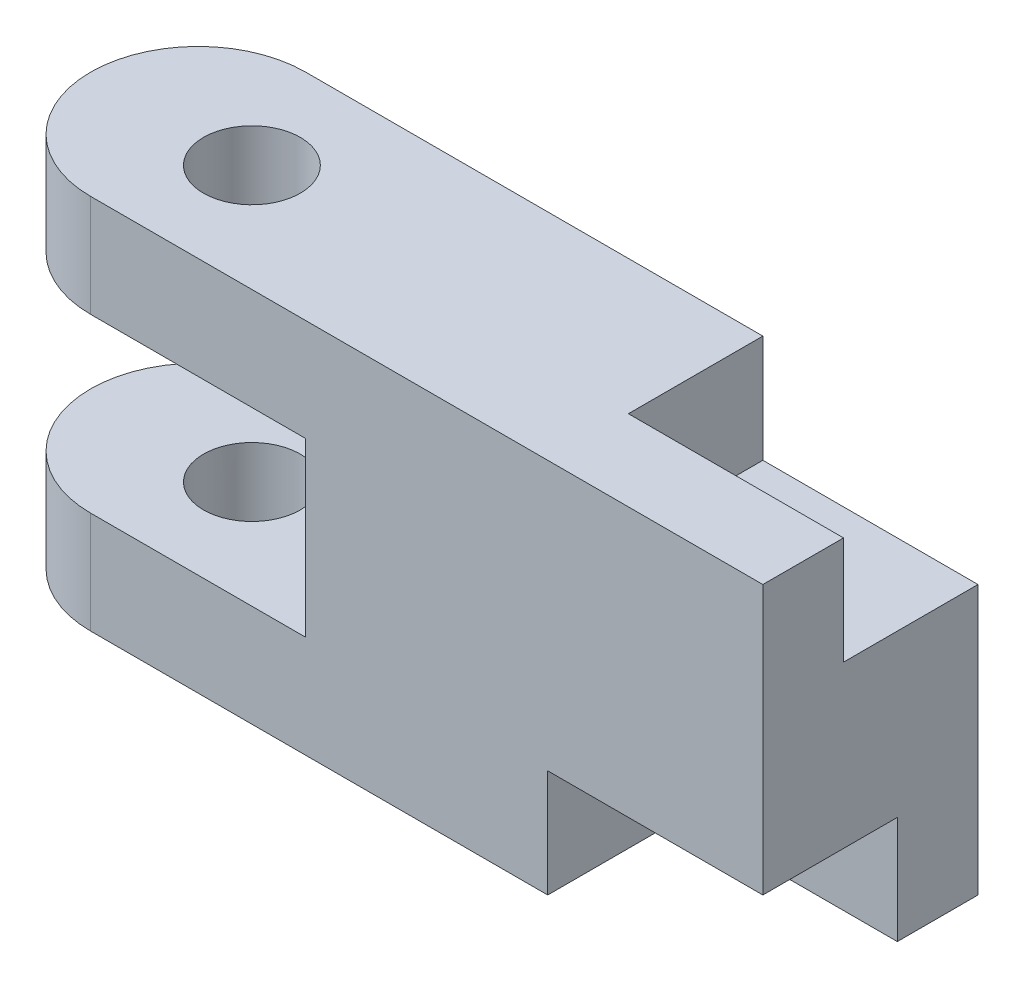
SolidWorks part; units mm, degrees
ref_plane "Front Plane" through (0, 0, 0) normal (0, 0, 1) x (1, 0, 0)
ref_plane "Top Plane" through (0, 0, 0) normal (0, 1, 0) x (1, 0, 0)
ref_plane "Right Plane" through (0, 0, 0) normal (1, 0, 0) x (0, 0, -1)
sketch "Sketch1" plane through (0, 0, 0) normal (0, 1, 0) x (1, 0, 0)
  line L1 (-1, 2) -> (11.5, 2)
  line L3 (-1, -2) -> (11.5, -2)
  line L4 (11.5, 2) -> (11.5, -2)
  line L5 (5.25, -2) -> (5.25, 2) construction
  line L6 (0, 0) -> (11.5, 0) construction
  circle A0 centre (0, 0) radius 0.9
  arc A2 (-1, 2) -> (-1, -2) centre (-1, 0) ccw
  point P315 (5.25, 0)
  dimension "D1" = 1.8
  dimension "D5" = 2
  dimension "D2" = 4
  dimension "D3" = 12.5
  dimension "D4" = 1
extrude "Boss-Extrude1" add sketch "Sketch1" along normal blind 7
sketch "Sketch2" plane through (0, 0, 2) normal (0, 0, 1) x (1, 0, 0)
  line L0 (-3, 3.5) -> (11.5, 3.5) construction
  line L1 (-3, 7) -> (-3, 0) construction
  line L2 (11.5, 7) -> (11.5, 0) construction
  line L4 (-3, 5.1) -> (3, 5.1)
  line L5 (-3, 5.1) -> (-3, 1.9)
  line L6 (-3, 1.9) -> (3, 1.9)
  line L7 (3, 5.1) -> (3, 1.9)
  line L8 (0, 1.9) -> (0, 5.1) construction
  line L9 (-3, 3.5) -> (3, 3.5) construction
  point P290 (0, 3.5)
  dimension "D1" = 3.2
  dimension "D2" = 6
extrude "Cut-Extrude1" cut sketch "Sketch2" against normal up to next
sketch "Sketch3" plane through (11.5, 0, 0) normal (1, 0, 0) x (0, 0, -1)
  line L0 (0, 7) -> (0, 0) construction
  line L1 (-2, 7) -> (2, 7) construction
  line L6 (-2, 3.5) -> (2, 3.5) construction
  line L7 (-2, 7) -> (-2, 0) construction
  line L8 (2, 7) -> (2, 0) construction
  line L9 (-0.5, 7) -> (-0.5, 5)
  line L10 (-0.5, 5) -> (2, 5)
  line L11 (2, 5) -> (2, 7)
  line L12 (2, 7) -> (-0.5, 7)
  line L13 (-2, 0) -> (2, 0) construction
  line L14 (-2, 2) -> (0.5, 2)
  line L15 (-2, 2) -> (-2, 0)
  line L16 (-2, 0) -> (0.5, 0)
  line L17 (0.5, 2) -> (0.5, 0)
  line L18 (-0.75, 0) -> (-0.75, 2) construction
  line L19 (-2, 1) -> (0.5, 1) construction
  point P184 (-0.75, 1)
  dimension "D1" = 2
  dimension "D2" = 1.5
  dimension "D3" = 2
  dimension "D4" = 1.5
extrude "Cut-Extrude2" cut sketch "Sketch3" against normal blind 4
equation "\"D3@Sketch1\"=\"D4@Sketch1\"+10-2.8+4+0.3"
